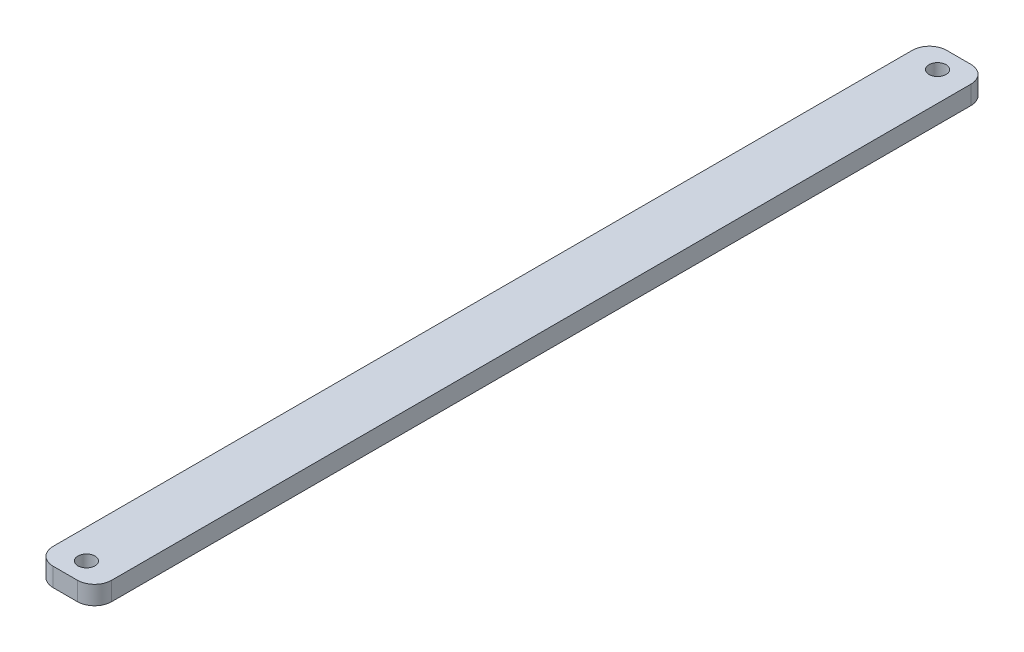
SolidWorks part; units mm, degrees
ref_plane "Front Plane" through (0, 0, 0) normal (0, 0, 1) x (1, 0, 0)
ref_plane "Top Plane" through (0, 0, 0) normal (0, 1, 0) x (1, 0, 0)
ref_plane "Right Plane" through (0, 0, 0) normal (1, 0, 0) x (0, 0, -1)
sketch "Sketch1" plane through (0, 0, 0) normal (0, 1, 0) x (1, 0, 0)
  line L0 (0, 0) -> (0, -72.58) construction
  line L1 (-5, 76.2) -> (5, 76.2)
  line L2 (-5, 76.2) -> (-5, -76.2)
  line L3 (-5, -76.2) -> (5, -76.2)
  line L4 (5, 76.2) -> (5, -76.2)
  line L5 (-5, 76.2) -> (5, -76.2) construction
  line L6 (-5, -76.2) -> (5, 76.2) construction
  line L7 (0, 72.58) -> (0, 0) construction
  circle A0 centre (0, 72.58) radius 1.4605
  circle A1 centre (0, -72.58) radius 1.4605
  point P0 (0, 0)
  point P11 (0, 0)
  dimension "D3" = 2.921
  dimension "D1" = 152.4
  dimension "D2" = 10
  dimension "D4" = 145.16
extrude "Boss-Extrude1" add sketch "Sketch1" along normal blind 3.175
fillet "Fillet1" radius 2.921 4 edges at (-5, 1.5875, -76.2) (5, 1.5875, -76.2) (-5, 1.5875, 76.2) (5, 1.5875, 76.2)
